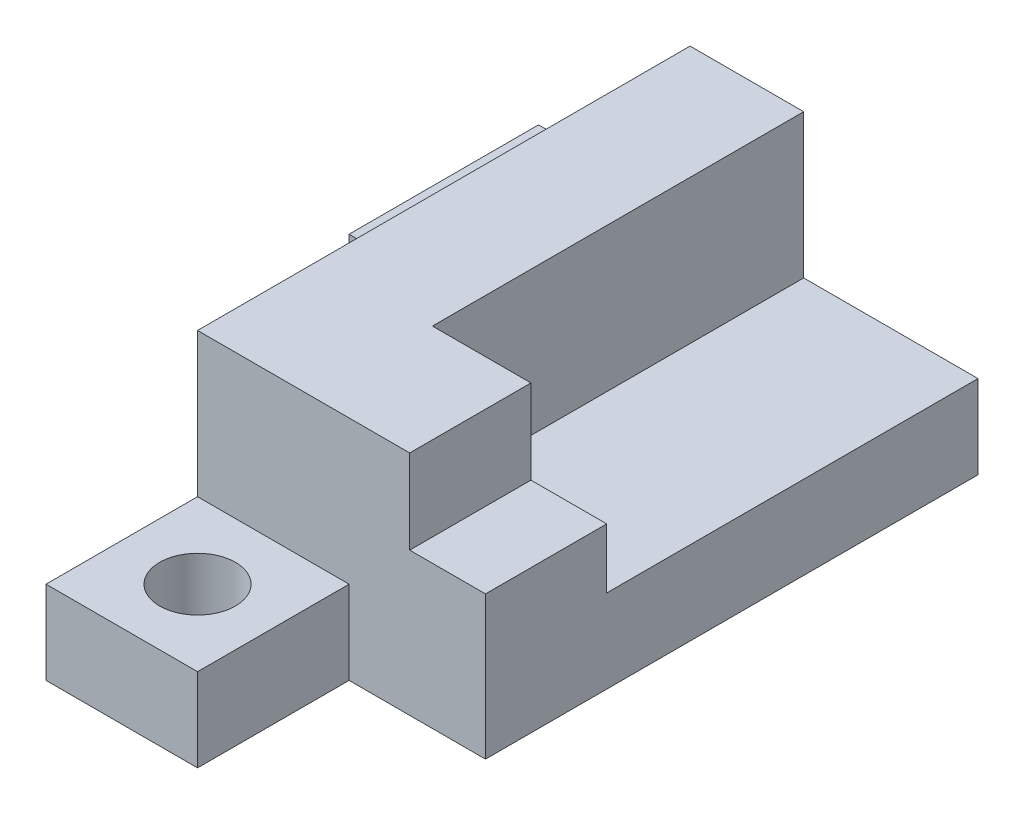
SolidWorks part; units mm, degrees
ref_plane "Front Plane" through (0, 0, 0) normal (0, 0, 1) x (1, 0, 0)
ref_plane "Top Plane" through (0, 0, 0) normal (0, 1, 0) x (1, 0, 0)
ref_plane "Right Plane" through (0, 0, 0) normal (1, 0, 0) x (0, 0, -1)
sketch "Sketch1" plane through (0, 0, 0) normal (0, 1, 0) x (1, 0, 0)
  line L1 (-184.5, -100) -> (184.5, -100)
  line L2 (-184.5, -100) -> (-184.5, 100)
  line L3 (-184.5, 100) -> (184.5, 100)
  line L4 (184.5, -100) -> (184.5, 100)
  line L5 (-184.5, -100) -> (184.5, 100) construction
  line L6 (-184.5, 100) -> (184.5, -100) construction
  point P0 (0, 0)
  dimension "D1" = 200
  dimension "353" = 369
extrude "Boss-Extrude1" add sketch "Sketch1" along normal blind 20
sketch "Sketch2" plane through (0, 20, 0) normal (0, 1, 0) x (1, 0, 0)
  line L0 (-184.5, -100) -> (184.5, -100) construction
  line L1 (-184.5, -100) -> (-169.5, -100)
  line L2 (-184.5, -100) -> (-184.5, -35)
  line L3 (-184.5, -35) -> (-169.5, -35)
  line L4 (-169.5, -84) -> (-169.5, -35)
  line L5 (-184.5, 100) -> (-169.5, 100)
  line L6 (-184.5, 100) -> (-184.5, 35)
  line L7 (-184.5, 35) -> (-169.5, 35)
  line L8 (-169.5, 84) -> (-169.5, 35)
  line L9 (-169.5, 100) -> (-119.5, 100)
  line L11 (-169.5, 84) -> (-119.5, 84)
  line L12 (-119.5, 100) -> (-119.5, 84)
  line L13 (-169.5, -100) -> (-119.5, -100)
  line L15 (-169.5, -84) -> (-119.5, -84)
  line L16 (-119.5, -100) -> (-119.5, -84)
  line L17 (-44.5, -100) -> (84.5, -100)
  line L18 (-44.5, -100) -> (-44.5, -84)
  line L19 (-44.5, -84) -> (84.5, -84)
  line L20 (84.5, -100) -> (84.5, -84)
  line L21 (184.5, 100) -> (-184.5, 100) construction
  line L22 (-44.5, 100) -> (84.5, 100)
  line L23 (-44.5, 100) -> (-44.5, 84)
  line L24 (-44.5, 84) -> (84.5, 84)
  line L25 (84.5, 100) -> (84.5, 84)
  line L26 (184.5, -100) -> (184.5, 100) construction
  point P28 (84.5, -92)
  dimension "D1" = 65
  dimension "D2" = 15
  dimension "D3" = 65
  dimension "D4" = 15
  dimension "D5" = 16
  dimension "D6" = 50
  dimension "D7" = 50
  dimension "D8" = 16
  dimension "D9" = 75
  dimension "D10" = 100
extrude "Boss-Extrude2" add sketch "Sketch2" along normal blind 10
sketch "Sketch3" plane through (0, 20, 0) normal (0, 1, 0) x (1, 0, 0)
  line L0 (-119.5, -84) -> (-169.5, -84) construction
  line L1 (-169.5, 84) -> (172.5, 84)
  line L2 (-169.5, 84) -> (-169.5, -84)
  line L3 (-169.5, -84) -> (172.5, -84)
  line L4 (172.5, 84) -> (172.5, -84)
  dimension "D1" = 342
extrude "Cut-Extrude1" cut sketch "Sketch3" against normal blind 9
sketch "Sketch4" plane through (0, 0, -100) normal (0, 0, -1) x (-1, 0, 0)
  line L0 (-84.5, 30) -> (44.5, 30) construction
  line L1 (-69.5, 20) -> (30.5, 20)
  line L2 (-69.5, 20) -> (-69.5, 30)
  line L3 (-69.5, 30) -> (30.5, 30)
  line L4 (30.5, 20) -> (30.5, 30)
  line L5 (-69.5, 20) -> (30.5, 30) construction
  line L6 (-69.5, 30) -> (30.5, 20) construction
  line L8 (-84.5, 30) -> (-84.5, 20) construction
  point P0 (-19.5, 25)
  dimension "D1" = 100
  dimension "D2" = 15
extrude "Boss-Extrude3" add sketch "Sketch4" along normal blind 60
sketch "Sketch6" plane through (0, 0, -84) normal (0, 0, 1) x (1, 0, 0)
  line L0 (-24.5, 30) -> (-26.0308, 28.0811)
  line L1 (-44.5, 30) -> (84.5, 30) construction
  line L2 (-25.1938, 26.3428) -> (-15.8062, 26.3428)
  line L3 (-14.9692, 28.0811) -> (-16.5, 30)
  line L4 (-16.5, 30) -> (-24.5, 30)
  line L5 (-44.5, 30) -> (84.5, 30) construction
  line L6 (-44.5, 30) -> (-44.5, 20) construction
  line L7 (56.5, 30) -> (54.982, 27.8015)
  line L8 (55.8062, 26.2309) -> (65.1938, 26.2309)
  line L9 (66.018, 27.8015) -> (64.5, 30)
  line L10 (64.5, 30) -> (56.5, 30)
  line L12 (84.5, 30) -> (84.5, 20) construction
  arc A0 (-26.0308, 28.0811) -> (-25.1938, 26.3428) centre (-25.1938, 27.4134) ccw
  arc A1 (-15.8062, 26.3428) -> (-14.9692, 28.0811) centre (-15.8062, 27.4134) ccw
  arc A2 (54.982, 27.8015) -> (55.8062, 26.2309) centre (55.8062, 27.2324) ccw
  arc A3 (65.1938, 26.2309) -> (66.018, 27.8015) centre (65.1938, 27.2324) ccw
  dimension "D1" = 8
  dimension "D2" = 20
  dimension "D3" = 8
  dimension "D4" = 20
extrude "Cut-Extrude3" cut sketch "Sketch6" against normal blind 60 and the other way blind 10
sketch "Sketch10" plane through (0, 30, 0) normal (0, 1, 0) x (1, 0, 0)
  line L1 (-146.5, 161.5046) -> (257.5, 161.5046)
  line L2 (-146.5, 161.5046) -> (-146.5, -163.2916)
  line L3 (-146.5, -163.2916) -> (257.5, -163.2916)
  line L4 (257.5, 161.5046) -> (257.5, -163.2916)
  line L6 (-184.5, 35) -> (-184.5, -35) construction
  dimension "D1" = 38
  dimension "D2" = 404
extrude "Cut-Extrude4" cut sketch "Sketch10" against normal blind 69
sketch "Sketch14" plane through (0, 0, -100) normal (0, 0, -1) x (-1, 0, 0)
  line L6 (119.5, 53.6124) -> (156.5, 53.6124)
  line L7 (119.5, 53.6124) -> (119.5, 18.895)
  line L8 (119.5, 18.895) -> (156.5, 18.895)
  line L9 (156.5, 53.6124) -> (156.5, 18.895)
  line L10 (184.5, 30) -> (184.5, 0) construction
  dimension "D1" = 28
extrude "Cut-Extrude7" cut sketch "Sketch14" against normal through all both and the other way through all
sketch "Sketch12" plane through (-184.5, 0, 0) normal (-1, 0, 0) x (0, 0, 1)
  line L1 (0, 0) -> (-50, 0)
  line L2 (0, 0) -> (0, 11)
  line L3 (0, 11) -> (-50, 11)
  line L4 (-50, 0) -> (-50, 11)
  dimension "D1" = 11
  dimension "D2" = 50
extrude "Boss-Extrude6" add sketch "Sketch12" along normal blind 20
sketch "Sketch13" plane through (0, 11, 0) normal (0, 1, 0) x (1, 0, 0)
  line L0 (-204.5, 0) -> (-204.5, 50) construction
  line L1 (-204.5, 50) -> (-184.5, 50) construction
  circle A0 centre (-194.5, 25) radius 4
  dimension "D1" = 10
  dimension "D2" = 25
extrude "Cut-Extrude6" cut sketch "Sketch13" against normal through all
sketch "Croquis3" plane through (0, 30, 0) normal (0, 1, 0) x (1, 0, 0)
  line L0 (16.1657, 0) -> (-146.5, 0)
  line L1 (-16.5, 0) -> (16.5, 0) construction
  line L2 (-146.5, -35) -> (-204.5, -35)
  line L3 (-146.5, 84) -> (-146.5, -84) construction
  line L4 (-204.5, 0) -> (-204.5, 50) construction
  line L5 (-204.5, -35) -> (-204.5, 35)
  line L7 (-146.5, 35) -> (-146.5, -35)
  line L8 (-146.5, 35) -> (-204.5, 35)
  line L9 (-204.5, 0) -> (-245.6879, 0)
  line M10 (-169.5, -35) -> (-184.5, -35)
extrude "Cortar-Extruir4" cut sketch "Croquis3" against normal blind 220 contours L7 L8 L5 L2 M10
sketch "Croquis5" plane through (0, 0, -50) normal (0, 0, -1) x (-1, 0, 0)
  line L0 (184.5, 11) -> (204.5, 11)
  line L1 (204.5, 11) -> (204.5, 0)
  line L2 (204.5, 0) -> (184.5, 0)
  line L3 (184.5, 0) -> (184.5, 11)
extrude "Saliente-Extruir2" add sketch "Croquis5" along normal blind 10
sketch "Croquis6" plane through (0, 0, -100) normal (0, 0, -1) x (-1, 0, 0)
  line L0 (184.5, 11) -> (164.5, 11)
  line L1 (164.5, 11) -> (164.5, 0)
  line L2 (146.5, 0) -> (184.5, 0) construction
  line L3 (164.5, 0) -> (184.5, 0)
  line L4 (184.5, 0) -> (184.5, 11)
  dimension "D1" = 20
extrude "Saliente-Extruir3" add sketch "Croquis6" along normal blind 20
sketch "Croquis8" plane through (0, 11, 0) normal (0, 1, 0) x (1, 0, 0)
  circle A0 centre (-194.5, 47.5) radius 5
  circle A1 centre (-194.5, -47.5) radius 5
  circle A2 centre (-174.5, -110) radius 5
  circle A3 centre (-174.5, 110) radius 5
  dimension "D1" = 10
  dimension "D2" = 10
  dimension "D3" = 10
  dimension "D4" = 10
extrude "Cortar-Extruir5" cut sketch "Croquis8" against normal blind 48
sketch "Croquis9" plane through (0, 30, 0) normal (0, 1, 0) x (1, 0, 0)
  line L0 (-184.5, -35) -> (-146.5, -35)
  line L1 (-146.5, -35) -> (-146.5, -100)
  line L2 (-146.5, -100) -> (-184.5, -100)
  line L3 (-184.5, -100) -> (-184.5, -35)
extrude "Cortar-Extruir6" cut sketch "Croquis9" against normal blind 85
sketch "Croquis10" plane through (0, 11, 0) normal (0, 1, 0) x (1, 0, 0)
  line L0 (-156.5, 35) -> (-156.5, 51)
  line L1 (-146.5, 35) -> (-169.5, 35) construction
  line L2 (-156.5, 51) -> (-146.5, 51)
  line L3 (-146.5, 84) -> (-146.5, 35) construction
  line L4 (-146.5, 51) -> (-146.5, 35)
  line L5 (-146.5, 35) -> (-156.5, 35)
  dimension "D1" = 16
extrude "Saliente-Extruir4" add sketch "Croquis10" along normal blind 7.89
sketch "Croquis11" plane through (-169.5, 0, 0) normal (1, 0, 0) x (0, 0, -1)
  line L0 (35, 30) -> (35, 11)
  line L1 (35, 11) -> (51, 11)
  line L2 (84, 11) -> (35, 11) construction
  line L3 (51, 11) -> (51, 30)
  line L4 (35, 30) -> (84, 30) construction
  line L5 (51, 30) -> (35, 30)
  dimension "D1" = 16
extrude "Saliente-Extruir5" add sketch "Croquis11" along normal blind 13
sketch "Croquis12" plane through (0, 18.895, 0) normal (0, 1, 0) x (1, 0, 0)
  line L0 (-164.5, 100) -> (-164.5, 84)
  line L1 (-169.5, 84) -> (-156.5, 84) construction
  line L2 (-164.5, 84) -> (-146.5, 84)
  line L3 (-146.5, 84) -> (-146.5, 100)
  line L4 (-146.5, 100) -> (-164.5, 100)
extrude "Cortar-Extruir10" cut sketch "Croquis12" against normal up to surface (7.895 mm away) and the other way blind 36.9 contours L4 L0 L2 L3 up to face at (-158, 11, -67.5)
sketch "Croquis13" plane through (0, 30, 0) normal (0, 1, 0) x (1, 0, 0)
  line L0 (-169.5, 84) -> (-169.5, 100)
  line L1 (-164.5, 100) -> (-184.5, 100) construction
  line L2 (-169.5, 100) -> (-164.5, 100)
  line L3 (-164.5, 100) -> (-164.5, 84)
  line L4 (-164.5, 84) -> (-169.5, 84)
extrude "Cortar-Extruir11" cut sketch "Croquis13" against normal up to surface (19 mm away) up to face at (-160.1667, 11, -78.3333)
sketch "Croquis14" plane through (-184.5, 0, 0) normal (-1, 0, 0) x (0, 0, 1)
  line L0 (-100, 11) -> (-100, 0)
  line L1 (-100, 0) -> (-75, 0)
  line L2 (-120, 0) -> (-60, 0) construction
  line L4 (-75, 0) -> (-75, 11)
  line L5 (-75, 11) -> (-100, 11)
  dimension "D1" = 25
extrude "Saliente-Extruir6" add sketch "Croquis14" along normal blind 20
sketch "Croquis15" plane through (0, 11, 0) normal (0, 1, 0) x (1, 0, 0)
  line L0 (-184.5, 60) -> (-204.5, 60)
  line L1 (-204.5, 60) -> (-204.5, 35)
  line L2 (-204.5, 35) -> (-184.5, 35)
  line L3 (-184.5, 35) -> (-184.5, 60)
extrude "Cortar-Extruir12" cut sketch "Croquis15" against normal through all contours L3 L0 L1 L2
sketch "Croquis16" plane through (0, 11, 0) normal (0, 1, 0) x (1, 0, 0)
  circle A0 centre (-194.5, 87.5) radius 5
  dimension "D1" = 10
extrude "Cortar-Extruir13" cut sketch "Croquis16" against normal through all contours A0
sketch "Croquis17" plane through (0, 11, 0) normal (0, 1, 0) x (1, 0, 0)
  line L2 (-184.5, 35) -> (-156.5, 35) construction
  line L3 (-164.5, 35) -> (-164.5, 15)
  line L4 (-184.5, 35) -> (-184.5, 15)
  line L5 (-184.5, 15) -> (-164.5, 15)
  line L6 (-184.5, 35) -> (-164.5, 35)
  dimension "D1" = 20
extrude "Saliente-Extruir7" add sketch "Croquis17" against normal blind 11
sketch "Croquis18" plane through (0, 11, 0) normal (0, 1, 0) x (1, 0, 0)
  line L0 (-164.5, 100) -> (-184.5, 100)
  line L1 (-184.5, 100) -> (-184.5, 120)
  line L2 (-184.5, 120) -> (-164.5, 120)
  line L3 (-164.5, 120) -> (-164.5, 100)
extrude "Cortar-Extruir14" cut sketch "Croquis18" against normal through all
sketch "Croquis19" plane through (0, 11, 0) normal (0, 1, 0) x (1, 0, 0)
  circle A0 centre (-174.5, 25) radius 5
  dimension "D1" = 10
extrude "Cortar-Extruir15" cut sketch "Croquis19" against normal through all
